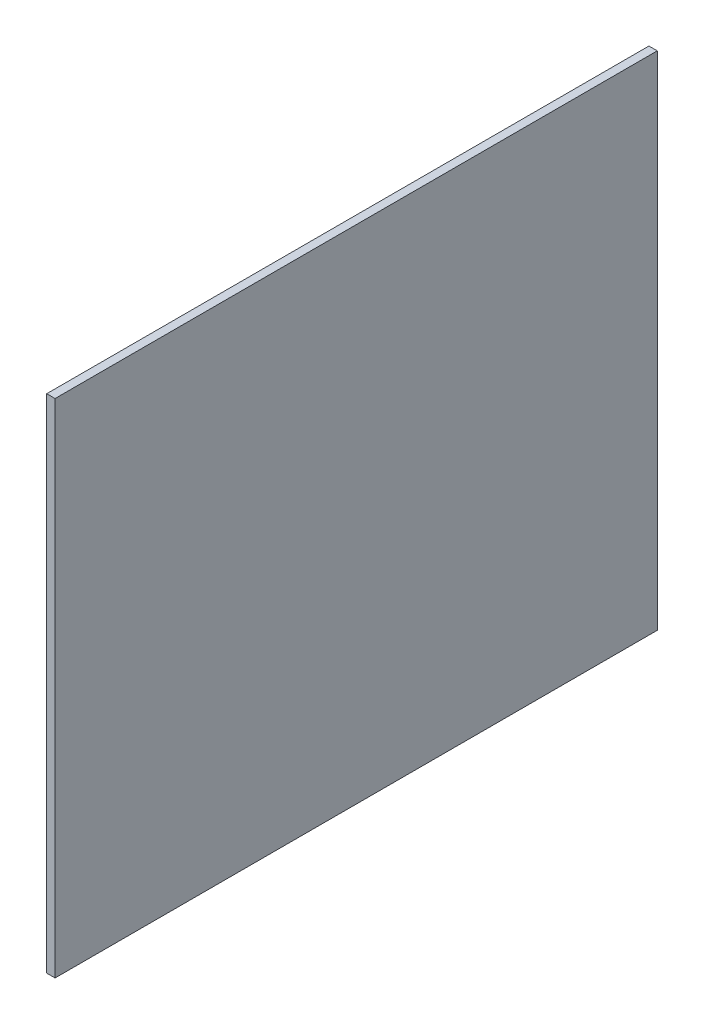
SolidWorks part; units mm, degrees
material "Vidro"
ref_plane "Plano frontal" through (0, 0, 0) normal (0, 0, 1) x (1, 0, 0)
ref_plane "Plano superior" through (0, 0, 0) normal (0, 1, 0) x (1, 0, 0)
ref_plane "Plano direito" through (0, 0, 0) normal (1, 0, 0) x (0, 0, -1)
sketch "Esboço1" plane through (0, 0, 0) normal (1, 0, 0) x (0, 0, -1)
  line L0 (0, 163.4259) -> (0, -163.4259) construction
  line L1 (-197.2222, 0) -> (197.2222, 0) construction
  line L2 (180, 150) -> (-180, 150)
  line L3 (-180, 150) -> (-180, -150)
  line L4 (180, -150) -> (-180, -150)
  line L5 (180, 150) -> (180, -150)
  dimension "D1" = 360
  dimension "D2" = 300
extrude "Ressalto-extrusão1" add sketch "Esboço1" along normal blind 5
